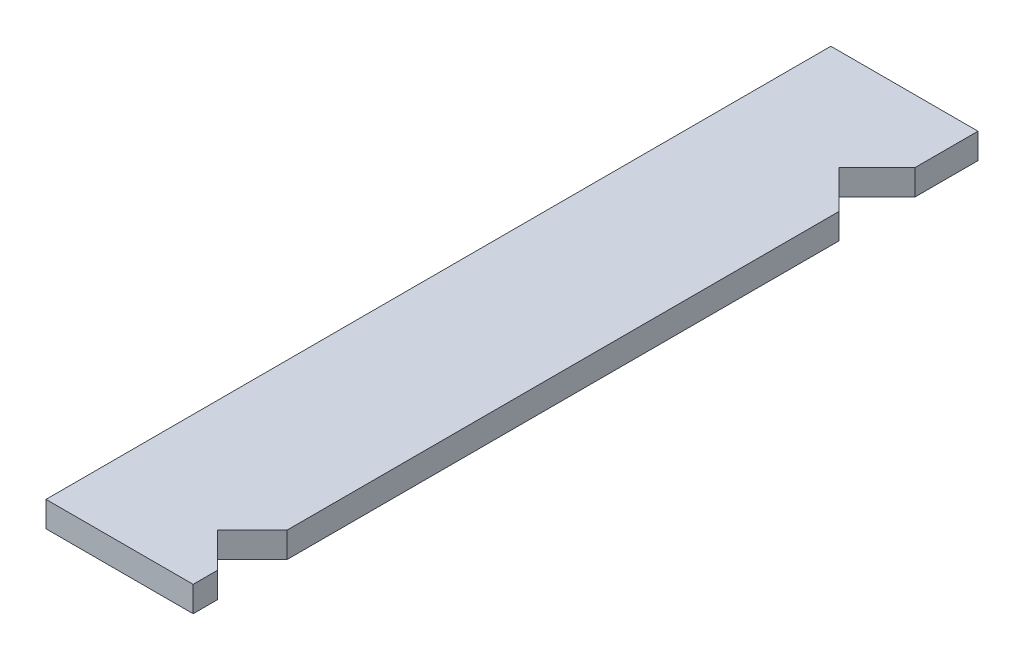
SolidWorks part; units mm, degrees
ref_plane "Front Plane" through (0, 0, 0) normal (0, 0, 1) x (1, 0, 0)
ref_plane "Top Plane" through (0, 0, 0) normal (0, 1, 0) x (1, 0, 0)
ref_plane "Right Plane" through (0, 0, 0) normal (1, 0, 0) x (0, 0, -1)
sketch "Sketch1" plane through (0, 0, 0) normal (0, 1, 0) x (1, 0, 0)
  line L1 (0, 0) -> (30, 0)
  line L2 (0, 0) -> (0, 160)
  line L3 (0, 160) -> (30, 160)
  line L4 (30, 0) -> (30, 160)
  dimension "D1" = 30
  dimension "D2" = 160
extrude "Boss-Extrude1" add sketch "Sketch1" along normal blind 5.2
sketch "Sketch2" plane through (0, 5.2, 0) normal (0, 1, 0) x (1, 0, 0)
  line L0 (30, 131.6421) -> (22.2218, 139.4203)
  line L5 (30, 19.1421) -> (22.9289, 12.0711)
  line L10 (30, 0) -> (30, 160) construction
  line L11 (22.9289, 12.0711) -> (30, 5)
  line L12 (30, 19.1421) -> (30, 5)
  line L13 (0, 0) -> (30, 0) construction
  line L14 (22.2218, 139.4203) -> (30, 147.1985)
  line L15 (30, 147.1985) -> (30, 131.6421)
  dimension "D1" = 45
  dimension "D2" = 5
  dimension "D3" = 10
  dimension "D4" = 45
  dimension "D5" = 11
  dimension "D6" = 112.5
extrude "Cut-Extrude1" cut sketch "Sketch2" against normal blind 10
equation "\"thick\"= 5.2'board thickness"
equation "\"fit\"= 0.3mm'fit adjustment"
equation "\"depth\"= \"thick\" * 1.5'cut depth"
equation "\"chamfer\"= \"thick\" / 2'fillet radius"
equation "\"width\"= \"thick\" - \"fit\"'cut width"
equation "\"gap\"= \"depth\" * 2'cut gap"
equation "\"curv\"= \"gap\" * 2'curvature radius"
equation "\"D1@Boss-Extrude1\"=\"thick\""
